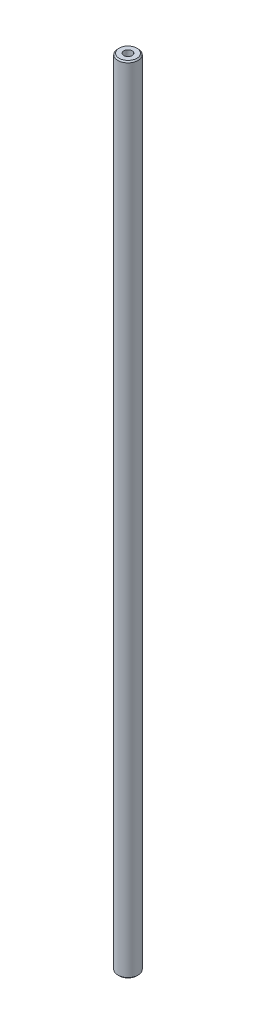
SolidWorks part; units mm, degrees
ref_plane "Front" through (0, 0, 0) normal (0, 0, 1) x (1, 0, 0)
ref_plane "Top" through (0, 0, 0) normal (0, 1, 0) x (1, 0, 0)
ref_plane "Right" through (0, 0, 0) normal (1, 0, 0) x (0, 0, -1)
sketch "Sketch1" plane through (0, 0, 0) normal (0, 1, 0) x (1, 0, 0)
  circle A0 centre (0, 0) radius 4
  dimension "D1" = 8
extrude "Boss-Extrude1" add sketch "Sketch1" along normal mid plane 315
chamfer "Chamfer1" distance 0.5 angle 45 2 edges at (0, -157.5, 4) (0, 157.5, 4)
sketch "Sketch2" plane through (0, 157.5, 0) normal (0, 1, 0) x (1, 0, 0)
  circle A0 centre (0, 0) radius 1.65
  dimension "D1" = 3.3
extrude "Cut-Extrude1" cut sketch "Sketch2" against normal blind 12
sketch "Sketch3" plane through (0, -157.5, 0) normal (0, -1, 0) x (1, 0, 0)
  circle A1 centre (0, 0) radius 1.65 construction
  circle A3 centre (0, 0) radius 1.65
extrude "Cut-Extrude2" cut sketch "Sketch3" against normal blind 12
